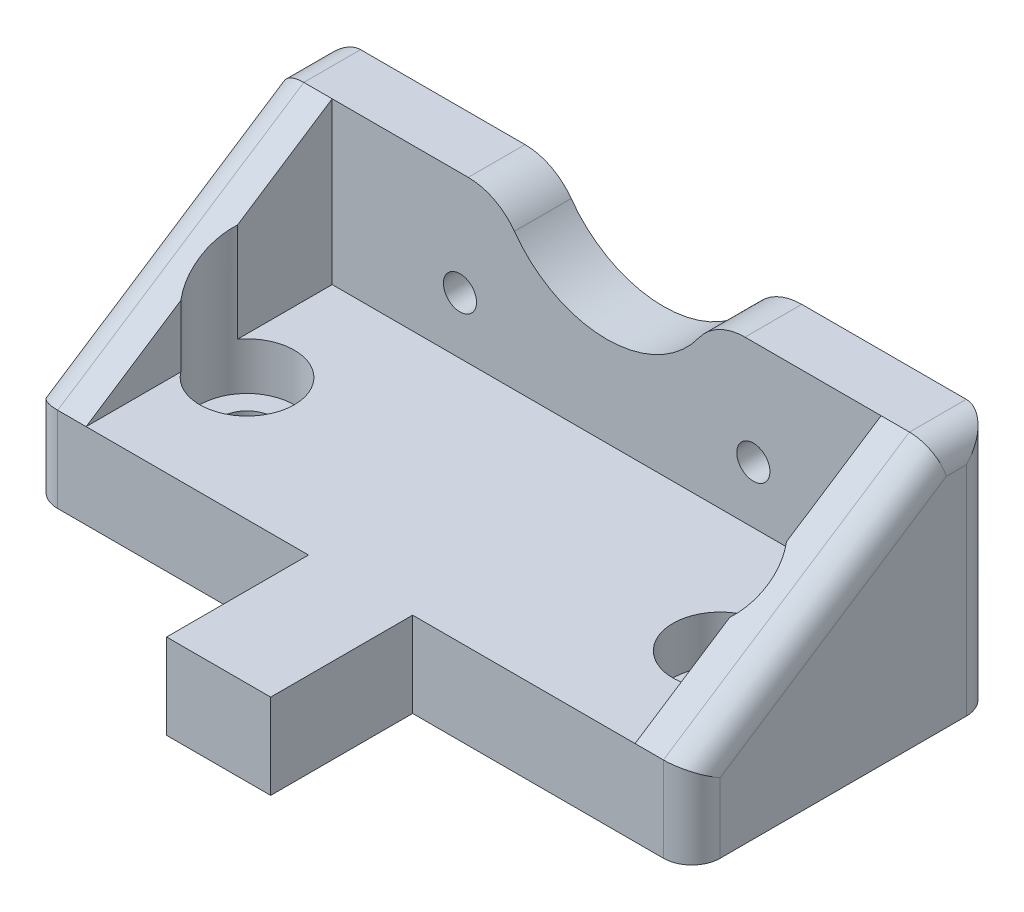
SolidWorks part; units mm, degrees
ref_plane "Front Plane" through (0, 0, 0) normal (0, 0, 1) x (1, 0, 0)
ref_plane "Top Plane" through (0, 0, 0) normal (0, 1, 0) x (1, 0, 0)
ref_plane "Right Plane" through (0, 0, 0) normal (1, 0, 0) x (0, 0, -1)
sketch "Sketch1" plane through (0, 0, 0) normal (0, 1, 0) x (1, 0, 0)
  line L0 (5.5, -16) -> (35, -16)
  line L1 (-35, 16) -> (35, 16)
  line L2 (-35, 16) -> (-35, -16)
  line L3 (-35, -16) -> (-5.5, -16)
  line L4 (35, 16) -> (35, -16)
  line L5 (-35, 16) -> (35, -16) construction
  line L6 (-35, -16) -> (35, 16) construction
  line L7 (-5.5, -31) -> (5.5, -31)
  line L8 (-5.5, -31) -> (-5.5, -16)
  line L10 (5.5, -31) -> (5.5, -16)
  line L11 (-5.5, -31) -> (5.5, -16) construction
  line L12 (-5.5, -16) -> (5.5, -31) construction
  point P0 (0, 0)
  point P6 (0, -23.5)
  dimension "D1" = 70
  dimension "D2" = 32
  dimension "D3" = 11
  dimension "D4" = 15
extrude "Boss-Extrude1" add sketch "Sketch1" along normal blind 9
sketch "Sketch2" plane through (0, 0, -16) normal (0, 0, -1) x (-1, 0, 0)
  line L0 (35, 9) -> (35, 0) construction
  line L1 (-35, 9) -> (35, 9)
  line L2 (-35, 9) -> (-35, 26)
  line L3 (-35, 26) -> (-14.6202, 26)
  line L4 (35, 9) -> (35, 26)
  line L5 (14.6202, 26) -> (35, 26)
  arc A0 (-9.7468, 23.5) -> (9.7468, 23.5) centre (0, 30.5) ccw
  arc A1 (-14.6202, 26) -> (-9.7468, 23.5) centre (-14.6202, 20) cw
  arc A2 (14.6202, 26) -> (9.7468, 23.5) centre (14.6202, 20) ccw
  point P15 (0, 18.5)
  dimension "D3" = 12
  dimension "D4" = 6
  dimension "D1" = 17
  dimension "D2" = 9.5
extrude "Boss-Extrude2" add sketch "Sketch2" against normal blind 6
sketch "Sketch3" plane through (35, 0, 0) normal (1, 0, 0) x (0, 0, -1)
  line L0 (-16, 9) -> (10, 26)
  line L1 (10, 26) -> (10, 9)
  line L2 (10, 9) -> (-16, 9)
extrude "Boss-Extrude3" add sketch "Sketch3" against normal blind 6
sketch "Sketch4" plane through (0, 9, 0) normal (0, 1, 0) x (1, 0, 0)
  line L0 (35, 10) -> (35, -16) construction
  line L1 (5.5, -16) -> (29, -16) construction
  circle A0 centre (25, -3) radius 2.75
  dimension "D1" = 5.5
  dimension "D2" = 10
  dimension "D3" = 13
extrude "Cut-Extrude1" cut sketch "Sketch4" against normal through all
sketch "Sketch5" plane through (0, 9, 0) normal (0, 1, 0) x (1, 0, 0)
  circle A0 centre (25, -3) radius 5
  dimension "D1" = 10
extrude "Cut-Extrude2" cut sketch "Sketch5" against normal blind 5 and the other way through all
sketch "Sketch6" plane through (0, 0, -10) normal (0, 0, 1) x (1, 0, 0)
  circle A0 centre (15.5, 15) radius 1.75
  arc A1 (-9.7468, 23.5) -> (9.7468, 23.5) centre (0, 30.5) ccw construction
  point P2 (0, 30.5)
  dimension "D1" = 3.5
  dimension "D2" = 15.5
  dimension "D3" = 15.5
extrude "Cut-Extrude3" cut sketch "Sketch6" against normal through all
mirror "Mirror1" about plane through (0, 0, 0) normal (1, 0, 0) of "Boss-Extrude3", "Cut-Extrude1", "Cut-Extrude2", "Cut-Extrude3"
fillet "Fillet1" radius 3 8 edges at (35, 4.5, 16) (35, 17.5, 3) (35, 26, -13) (35, 13, -16) (-35, 4.5, 16) (-35, 17.5, 3) (-35, 26, -13) (-35, 13, -16)
equation "\"D3@Sketch6\" = \"D2@Sketch6\""
